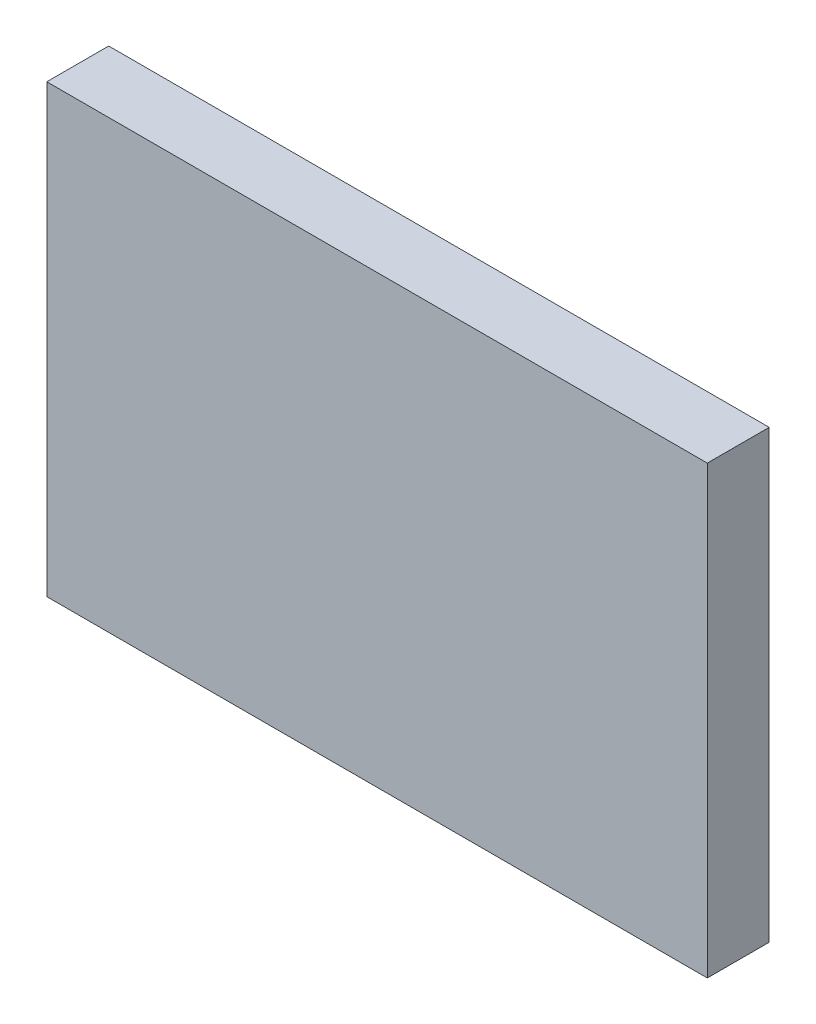
SolidWorks part; units mm, degrees
ref_plane "Alzado" through (0, 0, 0) normal (0, 0, 1) x (1, 0, 0)
ref_plane "Planta" through (0, 0, 0) normal (0, 1, 0) x (1, 0, 0)
ref_plane "Vista lateral" through (0, 0, 0) normal (1, 0, 0) x (0, 0, -1)
sketch "Croquis1" plane through (0, 0, 0) normal (0, 0, 1) x (1, 0, 0)
  line L0 (-43.45, -30.7) -> (43.45, -30.7) construction
  line L1 (-40.25, -24) -> (40.25, -24) construction
  line L2 (-40.25, -24) -> (-40.25, 24) construction
  line L3 (-40.25, 24) -> (40.25, 24) construction
  line L4 (40.25, -24) -> (40.25, 24) construction
  line L5 (-40.25, -24) -> (40.25, 24) construction
  line L6 (-40.25, 24) -> (40.25, -24) construction
  line L7 (-43.45, -30.7) -> (-43.45, 29.3) construction
  line L8 (-43.45, 29.3) -> (-40.25, 29.3) construction
  line L9 (-40.25, 29.3) -> (-40.25, 24) construction
  line L10 (0, 26.2147) -> (0, -39.3057) construction
  line L11 (43.45, -30.7) -> (43.45, 29.3) construction
  line L12 (43.45, 29.3) -> (40.25, 29.3) construction
  line L13 (40.25, 29.3) -> (40.25, 24) construction
  line L14 (-40.25, 24) -> (-43.45, 24)
  line L15 (40.25, -24) -> (-40.25, -24)
  line L16 (40.25, -24) -> (40.25, 29.3)
  line L17 (40.25, 29.3) -> (-40.25, 29.3)
  line L18 (-40.25, -24) -> (-40.25, 29.3)
  line L19 (-43.45, 24) -> (-43.45, -30.7)
  line L20 (-43.45, -30.7) -> (43.45, -30.7)
  line L21 (43.45, -30.7) -> (43.45, 24)
  line L22 (43.45, 24) -> (40.25, 24)
  line L24 (-48, 29.3) -> (48, 29.3)
  line L25 (-48, 29.3) -> (-48, -35.5116)
  line L26 (-48, -35.5116) -> (48, -35.5116)
  line L27 (48, 29.3) -> (48, -35.5116)
  point P0 (0, 0)
  dimension "D1" = 80.5
  dimension "D2" = 48
  dimension "D3" = 6.7
  dimension "D4" = 3.2
  dimension "D5" = 3.2
  dimension "D6" = 60
  dimension "D7" = 96
extrude "Saliente-Extruir1" add sketch "Croquis1" along normal blind 5 contours L27 L24 L16 L22 L21 L20 L19 L14 L18 L25 L26 | L18 L15 L16 L17
sketch "Croquis2" plane through (0, 0, 5) normal (0, 0, 1) x (1, 0, 0)
  line L1 (-48, 29.3) -> (48, 29.3)
  line L2 (-48, 29.3) -> (-48, -35.5116)
  line L3 (-48, -35.5116) -> (48, -35.5116)
  line L4 (48, 29.3) -> (48, -35.5116)
extrude "Saliente-Extruir2" add sketch "Croquis2" along normal blind 4
sketch "Croquis3" plane through (0, 0, 0) normal (0, 0, -1) x (-1, 0, 0)
  line L0 (-40.25, -24) -> (40.25, -24) construction
  line L1 (17.95, -24) -> (7.95, -24)
  line L2 (17.95, -24) -> (17.95, -39)
  line L3 (17.95, -39) -> (7.95, -39)
  line L4 (7.95, -24) -> (7.95, -39)
  line L6 (43.45, 24) -> (43.45, -30.7) construction
  dimension "D1" = 35.5
  dimension "D2" = 10
  dimension "D3" = 15
extrude "Cortar-Extruir1" cut sketch "Croquis3" against normal blind 6.8
sketch "Croquis4" plane through (0, 0, 0) normal (0, 0, -1) x (-1, 0, 0)
  line L0 (43.45, -30.7) -> (17.95, -30.7) construction
  line L1 (43.45, -30.7) -> (37.65, -30.7)
  line L2 (43.45, -30.7) -> (43.45, -28.2)
  line L3 (43.45, -28.2) -> (37.65, -28.2)
  line L4 (37.65, -30.7) -> (37.65, -28.2)
  line L5 (-43.45, -30.7) -> (-40.75, -30.7)
  line L6 (-43.45, -30.7) -> (-43.45, -28.2)
  line L7 (-43.45, -28.2) -> (-40.75, -28.2)
  line L8 (-40.75, -30.7) -> (-40.75, -28.2)
  line L12 (-43.45, -30.7) -> (7.95, -30.7)
  line L13 (7.95, -30.7) -> (7.95, -24)
  line L15 (7.95, -24) -> (-40.25, -24)
  line L21 (-40.25, -24) -> (-40.25, 24)
  line L22 (-40.25, 24) -> (-43.45, 24)
  line L23 (-43.45, 24) -> (-43.45, -30.7)
  line L24 (-43.45, -30.7) -> (-40.75, -30.7) construction
  line L35 (-43.45, -28.2) -> (-43.45, -30.7) construction
  point P3 (39.7094, -30.7)
  point P11 (0, 0)
  dimension "D2" = 5.8
  dimension "D3" = 2.5
  dimension "D4" = 2.7
  dimension "D5" = 2.5
  dimension "D1" = 0
extrude "Saliente-Extruir3" add sketch "Croquis4" against normal blind 7
sketch "Croquis5" plane through (0, 0, 0) normal (0, 0, -1) x (-1, 0, 0)
  line L1 (-35, -17.5) -> (35, -17.5)
  line L2 (-35, -17.5) -> (-35, 17.5)
  line L3 (-35, 17.5) -> (35, 17.5)
  line L4 (35, -17.5) -> (35, 17.5)
  line L5 (-35, -17.5) -> (35, 17.5) construction
  line L6 (-35, 17.5) -> (35, -17.5) construction
  point P0 (0, 0)
  dimension "D1" = 35
  dimension "D2" = 70
extrude "Cortar-Extruir2" cut sketch "Croquis5" against normal blind 5
